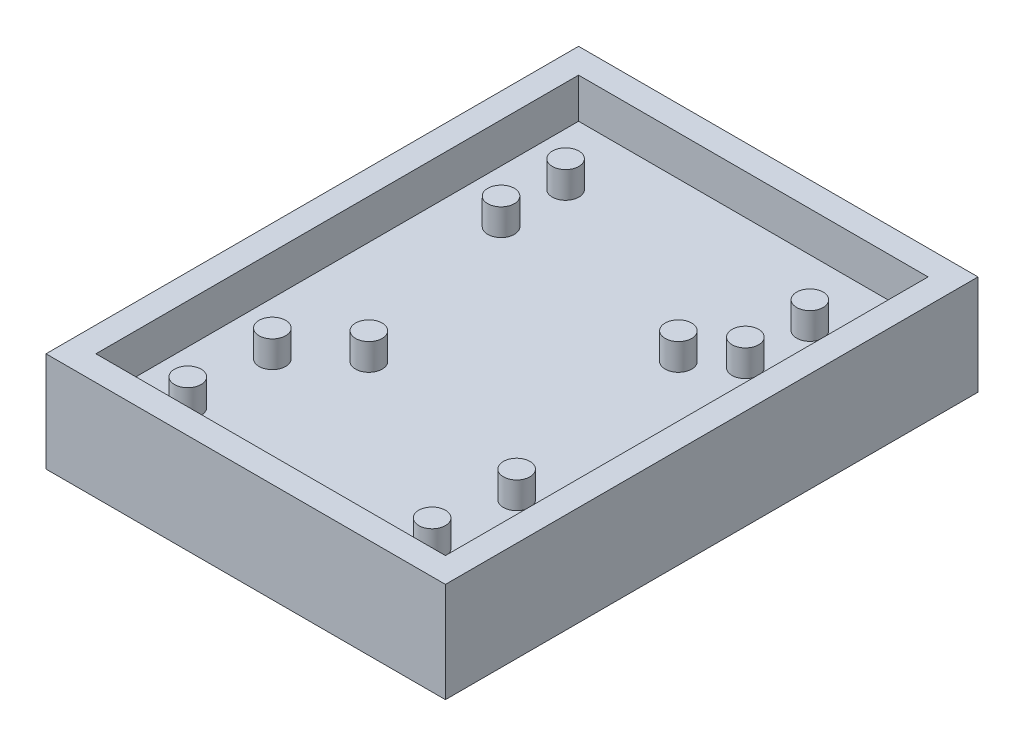
SolidWorks part; units mm, degrees
ref_plane "Front Plane" through (0, 0, 0) normal (0, 0, 1) x (1, 0, 0)
ref_plane "Top Plane" through (0, 0, 0) normal (0, 1, 0) x (1, 0, 0)
ref_plane "Right Plane" through (0, 0, 0) normal (1, 0, 0) x (0, 0, -1)
sketch "Sketch1" plane through (0, 0, 0) normal (0, 1, 0) x (1, 0, 0)
  line L1 (60, 80) -> (-60, 80)
  line L2 (60, 80) -> (60, -80)
  line L3 (60, -80) -> (-60, -80)
  line L4 (-60, 80) -> (-60, -80)
  line L5 (60, 80) -> (-60, -80) construction
  line L6 (60, -80) -> (-60, 80) construction
  point P0 (0, 0)
  dimension "D1" = 160
  dimension "D2" = 120
extrude "Boss-Extrude1" add sketch "Sketch1" along normal blind 30 contours L2 L1 L4 L3
sketch "Sketch2" plane through (0, 30, 0) normal (0, 1, 0) x (1, 0, 0)
  line L1 (-60, 80) -> (-52.5, 80) construction
  line L2 (-60, 80) -> (-60, 72.5) construction
  line L3 (-60, 72.5) -> (-52.5, 72.5) construction
  line L4 (-52.5, 80) -> (-52.5, 72.5) construction
  line L5 (60, -80) -> (52.5, -80) construction
  line L6 (60, -80) -> (60, -72.5) construction
  line L7 (60, -72.5) -> (52.5, -72.5) construction
  line L8 (52.5, -80) -> (52.5, -72.5) construction
  line L9 (-52.5, 72.5) -> (52.5, 72.5)
  line L10 (-52.5, 72.5) -> (-52.5, -72.5)
  line L11 (-52.5, -72.5) -> (52.5, -72.5)
  line L12 (52.5, 72.5) -> (52.5, -72.5)
  dimension "D1" = 7.5
  dimension "D2" = 7.5
  dimension "D3" = 7.5
  dimension "D4" = 7.5
extrude "Cut-Extrude1" cut sketch "Sketch2" against normal blind 12 contours L10 L9 L12 L11
sketch "Sketch3" plane through (0, 18, 0) normal (0, 1, 0) x (1, 0, 0)
  line L0 (21.5, 21.5) -> (21.5, 25) construction
  line L1 (25, -25) -> (-25, -25) construction
  line L2 (25, -25) -> (25, 25) construction
  line L3 (25, 25) -> (-25, 25) construction
  line L4 (-25, -25) -> (-25, 25) construction
  line L5 (25, -25) -> (-25, 25) construction
  line L6 (25, 25) -> (-25, -25) construction
  line L7 (-52.5, 72.5) -> (-45, 72.5) construction
  line L8 (-52.5, 72.5) -> (-52.5, 65) construction
  line L9 (-52.5, 65) -> (-45, 65) construction
  line L10 (-45, 72.5) -> (-45, 65) construction
  line L11 (52.5, -72.5) -> (45, -72.5) construction
  line L12 (52.5, -72.5) -> (52.5, -65) construction
  line L13 (52.5, -65) -> (45, -65) construction
  line L14 (45, -72.5) -> (45, -65) construction
  line L15 (-45, 65) -> (45, 65) construction
  line L16 (-45, 65) -> (-45, -65) construction
  line L17 (-45, -65) -> (45, -65) construction
  line L18 (45, 65) -> (45, -65) construction
  line L23 (-25, -25) -> (-21.5, -25) construction
  line L24 (-25, -25) -> (-25, -21.5) construction
  line L25 (-25, -21.5) -> (-21.5, -21.5) construction
  line L26 (-21.5, -25) -> (-21.5, -21.5) construction
  line L27 (21.5, 21.5) -> (25, 21.5) construction
  line L28 (25, 21.5) -> (25, 25) construction
  line L29 (21.5, 25) -> (25, 25) construction
  line L30 (0, -25) -> (0, -32) construction
  line L31 (0, -32) -> (0, -48) construction
  line L32 (0, 25) -> (0, 30) construction
  line L33 (40, -64) -> (-40, -64) construction
  line L34 (40, -64) -> (40, -32) construction
  line L35 (40, -32) -> (-40, -32) construction
  line L36 (-40, -64) -> (-40, -32) construction
  line L37 (40, -64) -> (-40, -32) construction
  line L38 (40, -32) -> (-40, -64) construction
  line L39 (0, 30) -> (0, 43.1096) construction
  line L40 (36.7, -60.7) -> (40, -60.7) construction
  line L41 (40, 30.1096) -> (-40, 30.1096) construction
  line L42 (40, 30.1096) -> (40, 56.1096) construction
  line L43 (40, 56.1096) -> (-40, 56.1096) construction
  line L44 (-40, 30.1096) -> (-40, 56.1096) construction
  line L45 (40, 30.1096) -> (-40, 56.1096) construction
  line L46 (40, 56.1096) -> (-40, 30.1096) construction
  line L47 (-40, -32) -> (-36.7, -32) construction
  line L48 (-40, -32) -> (-40, -35.3) construction
  line L49 (-40, -35.3) -> (-36.7, -35.3) construction
  line L50 (-36.7, -32) -> (-36.7, -35.3) construction
  line L51 (36.7, -60.7) -> (36.7, -64) construction
  line L52 (40, -60.7) -> (40, -64) construction
  line L53 (36.7, -64) -> (40, -64) construction
  line L54 (36.7, -32) -> (40, -32) construction
  line L55 (36.7, -32) -> (36.7, -35.3) construction
  line L56 (40, -32) -> (40, -35.3) construction
  line L57 (36.7, -35.3) -> (40, -35.3) construction
  line L58 (-40, -60.7) -> (-36.7, -60.7) construction
  line L59 (-40, -60.7) -> (-40, -64) construction
  line L60 (-36.7, -60.7) -> (-36.7, -64) construction
  line L61 (-40, -64) -> (-36.7, -64) construction
  line L63 (-40, 56.1096) -> (-36.7, 56.1096) construction
  line L64 (-40, 56.1096) -> (-40, 52.8096) construction
  line L65 (-40, 52.8096) -> (-36.7, 52.8096) construction
  line L66 (-36.7, 56.1096) -> (-36.7, 52.8096) construction
  line L67 (-40, 30.1096) -> (-36.7, 30.1096) construction
  line L68 (-40, 30.1096) -> (-40, 33.4096) construction
  line L69 (-40, 33.4096) -> (-36.7, 33.4096) construction
  line L70 (-36.7, 30.1096) -> (-36.7, 33.4096) construction
  line L71 (40, 30.1096) -> (36.7, 30.1096) construction
  line L72 (40, 30.1096) -> (40, 33.4096) construction
  line L73 (40, 33.4096) -> (36.7, 33.4096) construction
  line L74 (36.7, 30.1096) -> (36.7, 33.4096) construction
  line L75 (40, 56.1096) -> (36.7, 56.1096) construction
  line L76 (40, 56.1096) -> (40, 52.8096) construction
  line L77 (40, 52.8096) -> (36.7, 52.8096) construction
  line L78 (36.7, 56.1096) -> (36.7, 52.8096) construction
  circle A0 centre (-21.5, -21.5) radius 4
  circle A1 centre (25, 25) radius 4
  circle A2 centre (-36.7, -35.3) radius 4
  circle A3 centre (36.7, -35.3) radius 4
  circle A4 centre (36.7, -60.7) radius 4
  circle A5 centre (-36.7, -60.7) radius 4
  circle A6 centre (36.7, 33.4096) radius 4
  circle A7 centre (-36.7, 33.4096) radius 4
  circle A8 centre (-36.7, 52.8096) radius 4
  circle A9 centre (36.7, 52.8096) radius 4
  point P0 (0, 0)
  dimension "D8" = 8
  dimension "D19" = 3.3
  dimension "D20" = 8
  dimension "D1" = 50
  dimension "D2" = 50
  dimension "D3" = 7.5
  dimension "D4" = 7.5
  dimension "D5" = 7.5
  dimension "D6" = 7.5
  dimension "D7" = 3.5
  dimension "D9" = 7
  dimension "D10" = 16
  dimension "D11" = 80
  dimension "D12" = 32
  dimension "D13" = 80
  dimension "D14" = 26
  dimension "D15" = 3.3
  dimension "D16" = 3.3
  dimension "D17" = 3.3
  dimension "D18" = 3.3
extrude "Boss-Extrude2" add sketch "Sketch3" along normal blind 8
sketch "Sketch4" plane through (0, 26, 0) normal (0, 1, 0) x (1, 0, 0)
  circle A4 centre (-36.7, 52.8096) radius 2
  circle A5 centre (-36.7, 33.4096) radius 2
  circle A6 centre (25, 25) radius 2
  circle A7 centre (36.7, 33.4096) radius 2
  circle A8 centre (36.7, 52.8096) radius 2
  circle A9 centre (-21.5, -21.5) radius 2
  circle A10 centre (-36.7, -35.3) radius 2
  circle A11 centre (-36.7, -60.7) radius 2
  circle A12 centre (36.7, -60.7) radius 2
  circle A13 centre (36.7, -35.3) radius 2
